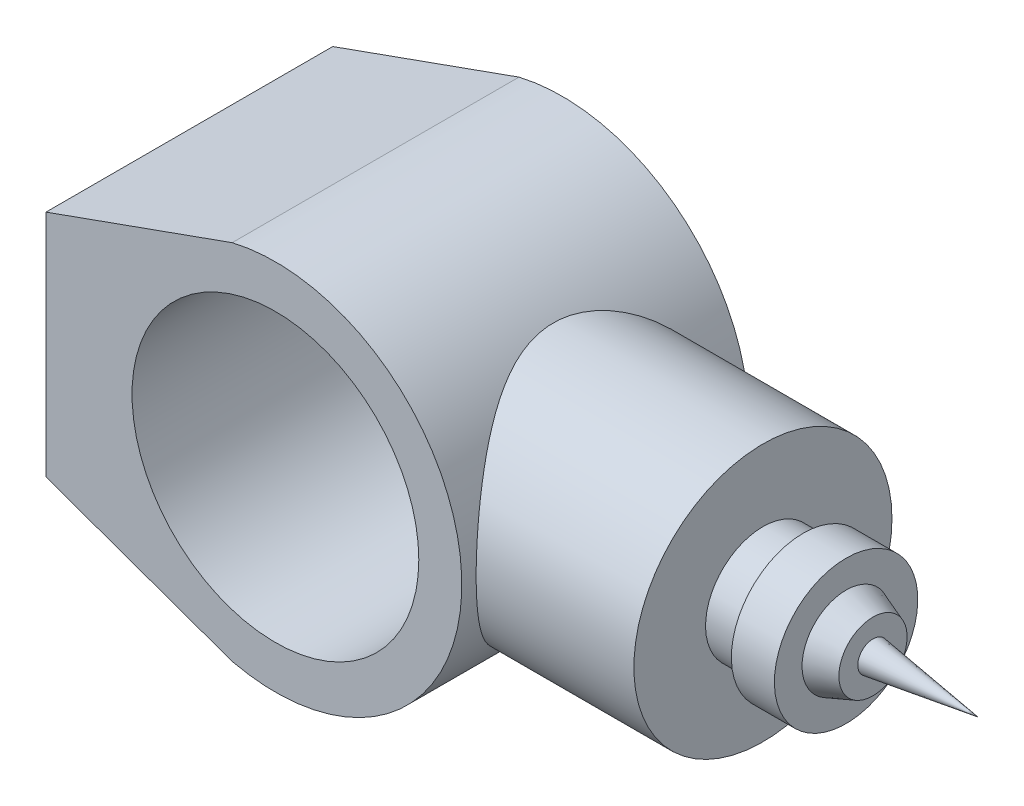
SolidWorks part; units mm, degrees
material "Cast Carbon Steel"
ref_plane "Front Plane" through (0, 0, 0) normal (0, 0, 1) x (1, 0, 0)
ref_plane "Top Plane" through (0, 0, 0) normal (0, 1, 0) x (1, 0, 0)
ref_plane "Right Plane" through (0, 0, 0) normal (1, 0, 0) x (0, 0, -1)
sketch "Sketch1" plane through (0, 0, 0) normal (0, 0, 1) x (1, 0, 0)
  line L0 (-80, -40) -> (-80, 40)
  line L1 (-80, 40) -> (-15.0669, 63.2297)
  line L2 (-80, -40) -> (-15.0669, -63.2297)
  circle A0 centre (0, 0) radius 50
  arc A1 (-15.0669, -63.2297) -> (-15.0669, 63.2297) centre (0, 0) ccw
  point P7 (-80, 0)
  dimension "D1" = 130
  dimension "D2" = 100
  dimension "D3" = 80
  dimension "D4" = 80
extrude "Boss-Extrude1" add sketch "Sketch1" along normal mid plane 100
ref_plane "Plane1" through (120, 0, 0) normal (1, 0, 0) x (0, 0, -1)
sketch "Sketch2" plane through (120, 0, 0) normal (1, 0, 0) x (0, 0, -1)
  circle A0 centre (0, 0) radius 45
  dimension "D1" = 90
extrude "Boss-Extrude2" add sketch "Sketch2" against normal up to next
sketch "Sketch3" plane through (0, 0, 0) normal (0, 0, 1) x (1, 0, 0)
  line L0 (120, 0) -> (120, -20)
  line L1 (120, -45) -> (120, 45) construction
  line L2 (120, -20) -> (134, -20)
  line L3 (134, -20) -> (134, -25)
  line L4 (134, -25) -> (149, -25)
  line L5 (149, -25) -> (149, -15.3535)
  line L6 (149, -15.3535) -> (158.3814, -11.8911)
  line L7 (158.3814, -11.8911) -> (158.3814, -5.2992)
  line L8 (158.3814, -5.2992) -> (195, 0)
  line L9 (195, 0) -> (120, 0)
  dimension "D1" = 20
  dimension "D2" = 14
  dimension "D3" = 5
  dimension "D4" = 15
  dimension "D5" = 10
  dimension "D6" = 37
  dimension "D7" = 75
revolve "Revolve1" add sketch "Sketch3" angle 360 about L9
